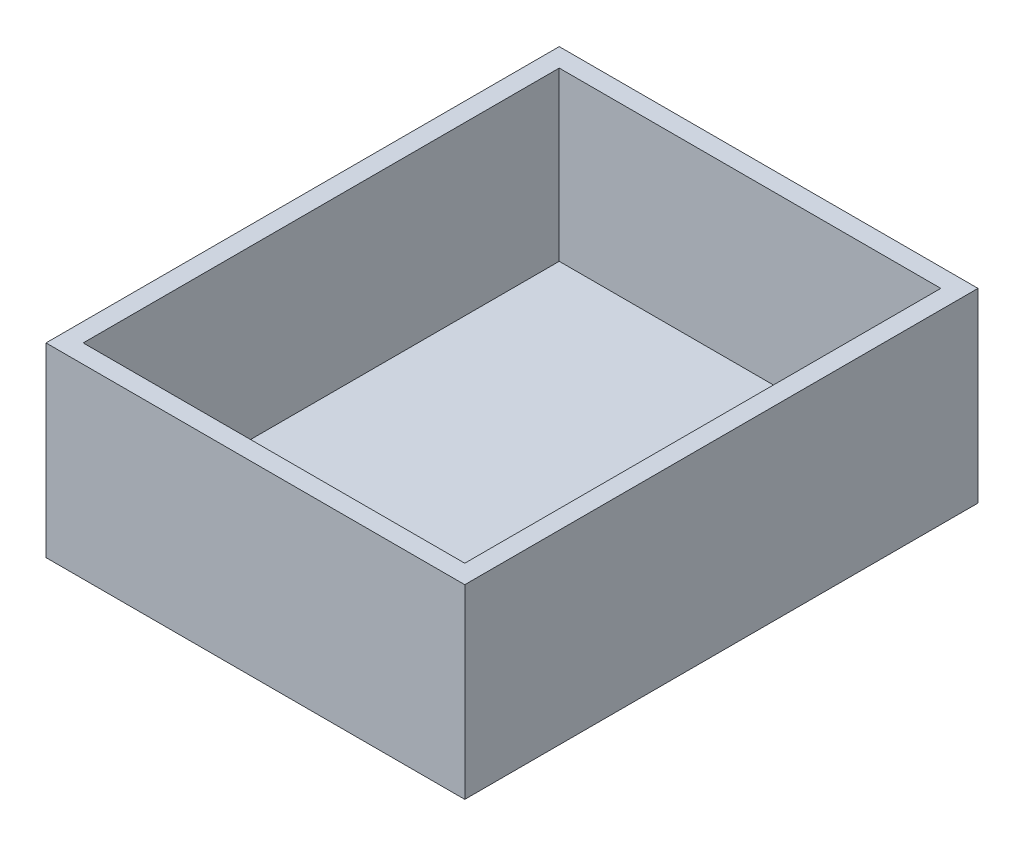
SolidWorks part; units mm, degrees
ref_plane "Front Plane" through (0, 0, 0) normal (0, 0, 1) x (1, 0, 0)
ref_plane "Top Plane" through (0, 0, 0) normal (0, 1, 0) x (1, 0, 0)
ref_plane "Right Plane" through (0, 0, 0) normal (1, 0, 0) x (0, 0, -1)
sketch "Sketch1" plane through (0, 0, 0) normal (0, 1, 0) x (1, 0, 0)
  line L1 (-41.3794, 83.4523) -> (60.2206, 83.4523)
  line L2 (-41.3794, 83.4523) -> (-41.3794, -43.5477)
  line L3 (-41.3794, -43.5477) -> (60.2206, -43.5477)
  line L4 (60.2206, 83.4523) -> (60.2206, -43.5477)
extrude "Boss-Extrude1" add sketch "Sketch1" along normal blind 5
sketch "Sketch4" plane through (0, 5, 0) normal (0, 1, 0) x (1, 0, 0)
  line L9 (60.7206, -44.0477) -> (-41.8794, -44.0477)
  line L10 (60.7206, -44.0477) -> (60.7206, 83.9523)
  line L11 (60.7206, 83.9523) -> (-41.8794, 83.9523)
  line L12 (-41.8794, -44.0477) -> (-41.8794, 83.9523)
extrude "Boss-Extrude3" add sketch "Sketch4" against normal up to surface (5 mm away) up to face at (9.4206, 0, -19.9523)
sketch "Sketch5" plane through (0, 0, 0) normal (0, -1, 0) x (1, 0, 0)
  line L17 (65.7206, -88.9523) -> (-46.8794, -88.9523)
  line L18 (65.7206, -88.9523) -> (65.7206, 49.0477)
  line L19 (65.7206, 49.0477) -> (-46.8794, 49.0477)
  line L20 (-46.8794, -88.9523) -> (-46.8794, 49.0477)
  line L21 (60.7206, -83.9523) -> (-41.8794, -83.9523)
  line L22 (60.7206, -83.9523) -> (60.7206, 44.0477)
  line L23 (60.7206, 44.0477) -> (-41.8794, 44.0477)
  line L24 (-41.8794, -83.9523) -> (-41.8794, 44.0477)
extrude "Boss-Extrude4" add sketch "Sketch5" against normal blind 50 contours L18 L17 L20 L19 | L22 L21 L24 L23
